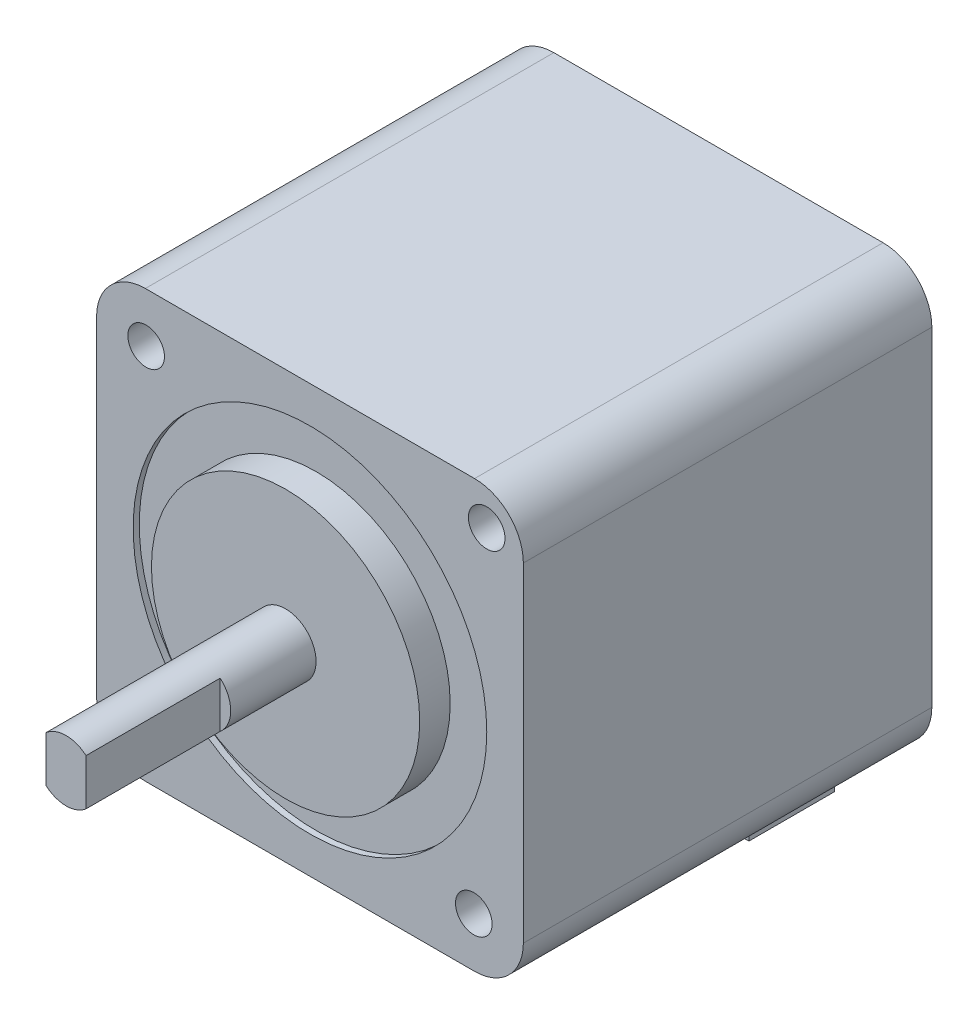
SolidWorks part; units mm, degrees
ref_plane "Front Plane" through (0, 0, 0) normal (0, 0, 1) x (1, 0, 0)
ref_plane "Top Plane" through (0, 0, 0) normal (0, 1, 0) x (1, 0, 0)
ref_plane "Right Plane" through (0, 0, 0) normal (1, 0, 0) x (0, 0, -1)
sketch "Sketch1" plane through (0, 0, 0) normal (0, 0, 1) x (1, 0, 0)
  line L1 (-17.5, 17.5) -> (17.5, 17.5)
  line L2 (-17.5, 17.5) -> (-17.5, -17.5)
  line L3 (-17.5, -17.5) -> (17.5, -17.5)
  line L4 (17.5, 17.5) -> (17.5, -17.5)
  line L5 (-17.5, 17.5) -> (17.5, -17.5) construction
  line L6 (-17.5, -17.5) -> (17.5, 17.5) construction
  point P0 (0, 0)
  dimension "D1" = 35
  dimension "D2" = 35
extrude "Boss-Extrude1" add sketch "Sketch1" along normal blind 33.5
sketch "Sketch2" plane through (0, 0, 33.5) normal (0, 0, 1) x (1, 0, 0)
  circle A0 centre (0, 0) radius 11
  dimension "D1" = 22
extrude "Boss-Extrude2" add sketch "Sketch2" along normal blind 2
sketch "Sketch3" plane through (0, 0, 33.5) normal (0, 0, 1) x (1, 0, 0)
  circle A0 centre (0, 0) radius 14.5
  circle A1 centre (0, 0) radius 11 construction
  circle A2 centre (0, 0) radius 11
  dimension "D1" = 29
extrude "Cut-Extrude1" cut sketch "Sketch3" against normal blind 0.5
fillet "Fillet1" radius 4 4 edges at (-17.5, 17.5, 16.75) (17.5, 17.5, 16.75) (17.5, -17.5, 16.75) (-17.5, -17.5, 16.75)
sketch "Sketch4" plane through (0, 0, 33.5) normal (0, 0, 1) x (1, 0, 0)
  line L0 (0, 23.622) -> (0, -24.5255) construction
  line L1 (0, 0) -> (25.4485, 25.4485) construction
  line L2 (0, 0) -> (-28.9914, -28.9914) construction
  line L3 (0, 0) -> (-24.4687, 24.4687) construction
  line L4 (0, 0) -> (26.1092, -26.1092) construction
  circle A0 centre (14.4957, 14.4957) radius 1.5
  circle A1 centre (-14.4957, -14.4957) radius 1.5
  circle A2 centre (-13.435, 13.435) radius 1.5
  circle A3 centre (13.435, -13.435) radius 1.5
  dimension "D3" = 3
  dimension "D4" = 20.5
  dimension "D6" = 3
  dimension "D7" = 19
  dimension "D1" = 45
  dimension "D2" = 90
  dimension "D5" = 20.5
  dimension "D8" = 19
extrude "Cut-Extrude2" cut sketch "Sketch4" against normal blind 5
sketch "Sketch5" plane through (0, 0, 35.5) normal (0, 0, 1) x (1, 0, 0)
  circle A0 centre (0, 0) radius 2.5
  dimension "D1" = 5
extrude "Boss-Extrude3" add sketch "Sketch5" along normal blind 18
sketch "Sketch6" plane through (0, 0, 53.5) normal (0, 0, 1) x (1, 0, 0)
  line L0 (1.6355, 1.8908) -> (1.6355, -1.8908)
  line L1 (-1.6355, 1.8908) -> (-1.6355, -1.8908)
  circle A0 centre (0, 0) radius 2.5 construction
  circle A1 centre (0, 0) radius 2.5 construction
  arc A2 (-1.6355, 1.8908) -> (-1.6355, -1.8908) centre (0, 0) ccw
  arc A3 (1.6355, -1.8908) -> (1.6355, 1.8908) centre (0, 0) ccw
extrude "Cut-Extrude3" cut sketch "Sketch6" against normal blind 11
sketch "Sketch7" plane through (0, -17.5, 0) normal (0, -1, 0) x (1, 0, 0)
  line L0 (-13.5, 0) -> (13.5, 0) construction
  line L1 (-10.5, 8) -> (10.5, 8)
  line L2 (-10.5, 8) -> (-10.5, 1)
  line L3 (-10.5, 1) -> (10.5, 1)
  line L4 (10.5, 8) -> (10.5, 1)
  line L5 (-10.5, 8) -> (10.5, 1) construction
  line L6 (-10.5, 1) -> (10.5, 8) construction
  point P0 (0, 4.5)
  dimension "D1" = 1
  dimension "D2" = 7
  dimension "D3" = 21
extrude "Boss-Extrude4" add sketch "Sketch7" along normal blind 5
